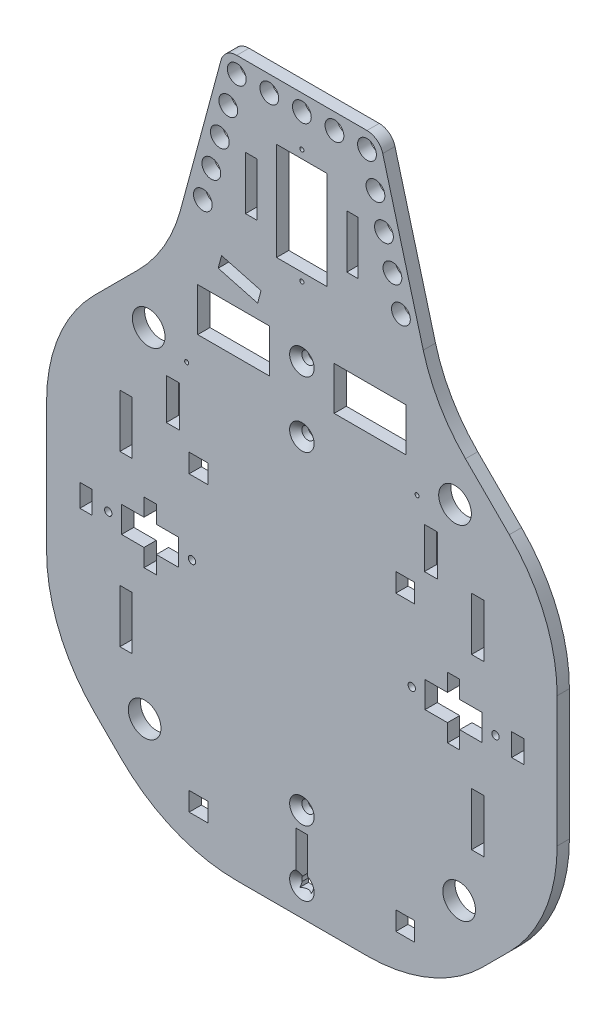
SolidWorks part; units mm, degrees
other "Popis1"
sketch "Skica4" plane through (-62.5, 107.5, 3) normal (-0.0791, 0.0312, 0.9964) x (0.9969, 0.0058, 0.079)
sketch "Skica5" plane through (-62.5, 107.5, 3) normal (-0.0791, 0.0312, 0.9964) x (0.9969, 0.0058, 0.079)
sketch "Skica6" plane through (-62.5, 112.5, 3) normal (-0.0791, 0.0312, 0.9964) x (0.9969, 0.0058, 0.079)
ref_plane "Přední rovina" through (0, 0, 0) normal (0, 0, 1) x (1, 0, 0)
ref_plane "Horní rovina" through (0, 0, 0) normal (0, 1, 0) x (1, 0, 0)
ref_plane "Pravá rovina" through (0, 0, 0) normal (1, 0, 0) x (0, 0, -1)
sketch "Skica1" plane through (0, 0, 0) normal (0, 0, 1) x (1, 0, 0)
  line L0 (-334.3708, 0) -> (16384.1714, 0) construction
  line L1 (0, -334.3708) -> (0, 16384.1714) construction
  line L2 (-44.3956, 7.5) -> (-44.3956, -7.5) construction
  line L3 (-62.5, -62.5) -> (62.5, -62.5) construction
  line L4 (-62.5, -62.5) -> (-62.5, 62.5) construction
  line L5 (-62.5, 62.5) -> (62.5, 62.5) construction
  line L6 (62.5, -62.5) -> (62.5, 62.5) construction
  line L7 (-62.5, -62.5) -> (62.5, 62.5) construction
  line L8 (-62.5, 62.5) -> (62.5, -62.5) construction
  line L9 (-44.3956, 7.5) -> (-61.3, 7.5) construction
  line L10 (-41.5478, 0) -> (-41.5478, 14.2) construction
  line L11 (-44.1478, 3.2) -> (-38.6478, 3.2)
  line L13 (-44.5478, 27.2) -> (-41.5478, 27.2)
  line L14 (-44.5478, 27.2) -> (-44.5478, 14.2)
  line L15 (-44.5478, 14.2) -> (-41.5478, 14.2)
  line L16 (-41.5478, 27.2) -> (-41.5478, 14.2)
  line L20 (-54.3478, 2.75) -> (-51.3478, 2.75)
  line L21 (-54.3478, 2.75) -> (-54.3478, -2.75)
  line L22 (-54.3478, -2.75) -> (-51.3478, -2.75)
  line L23 (-51.3478, 2.75) -> (-51.3478, -2.75)
  line L24 (-54.3478, 2.75) -> (-51.3478, -2.75) construction
  line L25 (-54.3478, -2.75) -> (-51.3478, 2.75) construction
  line L26 (-44.1478, 3.2) -> (-30.1478, 3.2) construction
  line L27 (-44.1478, 3.2) -> (-44.1478, -3.2)
  line L28 (-44.1478, -3.2) -> (-30.1478, -3.2) construction
  line L29 (-30.1478, 3.2) -> (-30.1478, -3.2)
  line L30 (-44.1478, 3.2) -> (-30.1478, -3.2) construction
  line L31 (-44.1478, -3.2) -> (-30.1478, 3.2) construction
  line L32 (-38.6478, -7.5) -> (-35.6478, -7.5)
  line L33 (-38.6478, -7.5) -> (-38.6478, 7.5) construction
  line L34 (-38.6478, 7.5) -> (-35.6478, 7.5)
  line L35 (-35.6478, -7.5) -> (-35.6478, 7.5) construction
  line L36 (-38.6478, -7.5) -> (-35.6478, 7.5) construction
  line L37 (-38.6478, 7.5) -> (-35.6478, -7.5) construction
  line L38 (-38.6478, 3.2) -> (-38.6478, 7.5)
  line L39 (-35.6478, 7.5) -> (-35.6478, 3.2)
  line L40 (-35.6478, 3.2) -> (-30.1478, 3.2)
  line L41 (-30.1478, -3.2) -> (-35.6478, -3.2)
  line L42 (-35.6478, -3.2) -> (-35.6478, -7.5)
  line L43 (-38.6478, -7.5) -> (-38.6478, -3.2)
  line L44 (-38.6478, -3.2) -> (-44.1478, -3.2)
  line L45 (-41.5478, -27.2) -> (-41.5478, -14.2)
  line L46 (-44.5478, -27.2) -> (-41.5478, -27.2)
  line L47 (-44.5478, -27.2) -> (-44.5478, -14.2)
  line L48 (-44.5478, -14.2) -> (-41.5478, -14.2)
  line L49 (-62.5, -32.5) -> (-62.5, 32.5)
  line L50 (-62.5, 32.5) -> (-32.5, 62.5)
  line L51 (-62.5, -32.5) -> (-32.5, -62.5)
  line L52 (-32.5, -62.5) -> (32.5, -62.5)
  line L54 (38.6478, -7.5) -> (35.6478, -7.5)
  line L55 (38.6478, -7.5) -> (38.6478, -3.2)
  line L56 (35.6478, -3.2) -> (35.6478, -7.5)
  line L57 (30.1478, -3.2) -> (35.6478, -3.2)
  line L58 (38.6478, -3.2) -> (44.1478, -3.2)
  line L59 (30.1478, 3.2) -> (30.1478, -3.2)
  line L60 (35.6478, 3.2) -> (30.1478, 3.2)
  line L61 (38.6478, 7.5) -> (35.6478, 7.5)
  line L62 (35.6478, 7.5) -> (35.6478, 3.2)
  line L63 (38.6478, 3.2) -> (38.6478, 7.5)
  line L64 (44.1478, 3.2) -> (44.1478, -3.2)
  line L65 (44.1478, 3.2) -> (38.6478, 3.2)
  line L66 (51.3478, 2.75) -> (51.3478, -2.75)
  line L67 (54.3478, -2.75) -> (51.3478, -2.75)
  line L68 (54.3478, 2.75) -> (54.3478, -2.75)
  line L69 (54.3478, 2.75) -> (51.3478, 2.75)
  line L70 (41.5478, 27.2) -> (41.5478, 14.2)
  line L71 (44.5478, 14.2) -> (41.5478, 14.2)
  line L72 (44.5478, 27.2) -> (44.5478, 14.2)
  line L73 (44.5478, 27.2) -> (41.5478, 27.2)
  line L74 (44.5478, -14.2) -> (41.5478, -14.2)
  line L75 (44.5478, -27.2) -> (44.5478, -14.2)
  line L76 (44.5478, -27.2) -> (41.5478, -27.2)
  line L77 (41.5478, -27.2) -> (41.5478, -14.2)
  line L78 (62.5, -32.5) -> (32.5, -62.5)
  line L79 (62.5, -32.5) -> (62.5, 32.5)
  line L80 (62.5, 32.5) -> (32.5, 62.5)
  line L81 (25.5, 59.1) -> (25.5, 48.5)
  line L86 (-8.8, 34.1) -> (8.8, 23.5) construction
  line L87 (-8.8, 23.5) -> (8.8, 34.1) construction
  line L88 (-25.5, 59.1) -> (-7.9, 59.1)
  line L89 (-25.5, 59.1) -> (-25.5, 48.5)
  line L90 (-25.5, 48.5) -> (-7.9, 48.5)
  line L91 (-7.9, 59.1) -> (-7.9, 48.5)
  line L92 (7.9, 59.1) -> (7.9, 48.5)
  line L93 (25.5, 48.5) -> (7.9, 48.5)
  line L94 (25.5, 59.1) -> (7.9, 59.1)
  line L95 (-6.2, 74.5) -> (-6.2, 98.5)
  line L96 (-6.2, 98.5) -> (6.2, 98.5)
  line L97 (6.2, 98.5) -> (6.2, 74.5)
  line L98 (6.2, 74.5) -> (-6.2, 74.5)
  line L99 (-11, 93) -> (-11, 80)
  line L100 (-11, 80) -> (-13.8, 80)
  line L101 (-13.8, 80) -> (-13.8, 93)
  line L102 (-13.8, 93) -> (-11, 93)
  line L107 (-20.4875, 65.0882) -> (-10.8282, 62.5)
  line L108 (-10.8282, 62.5) -> (-10, 65.591)
  line L109 (-10, 65.591) -> (-19.6593, 68.1792)
  line L110 (-19.6593, 68.1792) -> (-20.4875, 65.0882)
  line L111 (-6.2, 86.5) -> (6.2, 86.5) construction
  line L112 (-6.2, 86.5) -> (-11, 86.5) construction
  line L113 (11, 80) -> (13.8, 80)
  line L114 (11, 93) -> (11, 80)
  line L115 (13.8, 93) -> (11, 93)
  line L116 (13.8, 80) -> (13.8, 93)
  line L117 (30, 26) -> (33.2, 26)
  line L118 (-30, 36) -> (-33.2, 36)
  line L119 (-30, 36) -> (-30, 26)
  line L120 (-30, 26) -> (-33.2, 26)
  line L121 (-33.2, 36) -> (-33.2, 26)
  line L122 (33.2, 36) -> (33.2, 26)
  line L123 (30, 36) -> (33.2, 36)
  line L124 (30, 36) -> (30, 26)
  line L125 (-32.5, 62.5) -> (-19.0034, 112.5)
  line L126 (-19.0034, 112.5) -> (19.0034, 112.5)
  line L129 (0, 108.5) -> (7.97, 108.5) construction
  line L137 (32.5, 62.5) -> (19.0034, 112.5)
  line L138 (-15.94, 108.5) -> (-28.3568, 62.5) construction
  line L140 (-25.3, -51.5) -> (25.3, -51.5) construction
  line L141 (-25.3, -51.5) -> (-25.3, 20.23) construction
  line L142 (-25.3, 20.23) -> (25.3, 20.23) construction
  line L143 (25.3, -51.5) -> (25.3, 20.23) construction
  line L144 (-25.3, -51.5) -> (25.3, 20.23) construction
  line L145 (-25.3, 20.23) -> (25.3, -51.5) construction
  line L146 (-25.3, -15.635) -> (25.3, -15.635) construction
  line L147 (23, 22.53) -> (27.6, 22.53)
  line L148 (23, 22.53) -> (23, 17.93)
  line L149 (23, 17.93) -> (27.6, 17.93)
  line L150 (27.6, 22.53) -> (27.6, 17.93)
  line L151 (23, 22.53) -> (27.6, 17.93) construction
  line L152 (23, 17.93) -> (27.6, 22.53) construction
  line L153 (23, -49.2) -> (27.6, -49.2)
  line L154 (27.6, -53.8) -> (27.6, -49.2)
  line L155 (23, -53.8) -> (27.6, -53.8)
  line L156 (23, -53.8) -> (23, -49.2)
  line L157 (-23, -53.8) -> (-27.6, -53.8)
  line L158 (-23, -53.8) -> (-23, -49.2)
  line L159 (-27.6, -53.8) -> (-27.6, -49.2)
  line L160 (-23, -49.2) -> (-27.6, -49.2)
  line L161 (-23, 22.53) -> (-23, 17.93)
  line L162 (-23, 22.53) -> (-27.6, 22.53)
  line L163 (-27.6, 22.53) -> (-27.6, 17.93)
  line L164 (-23, 17.93) -> (-27.6, 17.93)
  line L165 (37.1478, 7.5) -> (37.1478, -7.5) construction
  circle A0 centre (-52.8478, 0) radius 11.3 construction
  circle A1 centre (0, 100.5) radius 0.5
  circle A3 centre (0, 72.5) radius 0.5
  circle A4 centre (0, 108.5) radius 2.3
  circle A5 centre (7.97, 108.5) radius 2.3
  circle A6 centre (15.94, 108.5) radius 2.3
  circle A7 centre (-15.94, 108.5) radius 2.3
  circle A8 centre (-7.97, 108.5) radius 2.3
  circle A9 centre (-15.94, 108.5) radius 2.3 construction
  circle A10 centre (-18.017, 100.8054) radius 2.3
  circle A11 centre (-20.094, 93.1108) radius 2.3
  circle A12 centre (-22.171, 85.4162) radius 2.3
  circle A13 centre (-24.2481, 77.7216) radius 2.3
  circle A14 centre (24.2481, 77.7216) radius 2.3
  circle A15 centre (22.171, 85.4162) radius 2.3
  circle A16 centre (20.094, 93.1108) radius 2.3
  circle A17 centre (18.017, 100.8054) radius 2.3
  circle A18 centre (47.3978, 0) radius 0.9
  circle A19 centre (26.8978, 0) radius 0.9
  circle A20 centre (-47.3978, 0) radius 0.9
  circle A21 centre (-26.8978, 0) radius 0.9
  point P4 (0, 0)
  point P15 (-52.8478, 0)
  point P17 (-37.1478, 0)
  point P27 (-37.1478, 0)
  point P46 (52.8478, 0)
  point P48 (0, 28.8)
  point P49 (0, -62.5)
  point P78 (0, 62.5)
  point P138 (0, 112.5)
  point P149 (-15.94, 108.5)
  point P156 (0, -15.635)
  dimension "D3" = 13
  dimension "D6" = 22.6
  dimension "D30" = 1
  dimension "D40" = 4.6
  dimension "D44" = 4
  dimension "D53" = 1.8
  dimension "D1" = 125
  dimension "D2" = 125
  dimension "D4" = 3
  dimension "D5" = 14.2
  dimension "D7" = 15
  dimension "D8" = 1.2
  dimension "D9" = 3
  dimension "D10" = 5.5
  dimension "D11" = 6.8
  dimension "D12" = 14
  dimension "D13" = 6.4
  dimension "D14" = 3
  dimension "D15" = 15
  dimension "D17" = 65
  dimension "D18" = 45
  dimension "D20" = 17.6
  dimension "D21" = 10.6
  dimension "D22" = 7.9
  dimension "D24" = 12.4
  dimension "D25" = 24
  dimension "D26" = 13
  dimension "D27" = 2.8
  dimension "D28" = 11
  dimension "D29" = 12
  dimension "D31" = 2
  dimension "D32" = 10
  dimension "D33" = 3.2
  dimension "D34" = 10
  dimension "D35" = 15
  dimension "D36" = 3.2
  dimension "D37" = 10
  dimension "D38" = 30
  dimension "D39" = 26
  dimension "D42" = 7.97
  dimension "D43" = 4
  dimension "D45" = 8
  dimension "D46" = 74.894
  dimension "D47" = 2
  dimension "D48" = 71.73
  dimension "D49" = 50.6
  dimension "D50" = 11
  dimension "D51" = 4.6
  dimension "D52" = 10.25
  dimension "D54" = 14.2
  dimension "D41" = 3
extrude "Přidat vysunutím1" add sketch "Skica1" along normal blind 3
sketch "Skica2" plane through (0, 0, 0) normal (0, 0, 1) x (1, 0, 0)
  line L0 (0, -1000) -> (0, 49000) construction
  line L1 (-1000, 0) -> (49000, 0) construction
  line L2 (8.8, 34.1) -> (-8.8, 34.1) construction
  circle A0 centre (0, 39.6) radius 1.5
  circle A1 centre (0, 55.6) radius 1.5
  circle A2 centre (0, -55.6) radius 1.5
  circle A3 centre (0, -39.6) radius 1.5
  dimension "D3" = 3
  dimension "D1" = 5.5
  dimension "D2" = 16
extrude "Odebrat vysunutím1" cut sketch "Skica2" along normal up to surface (3 mm away) up to face at (-25.3, -51.5, 3)
chamfer "Zkosení1" distance 1.5 angle 45 4 edges at (-1.5, -55.6, 3) (-1.5, -39.6, 3) (-1.5, 39.6, 3) (-1.5, 55.6, 3)
fillet "Zaoblit1" radius 40 8 edges at (-62.5, -32.5, 1.5) (-32.5, -62.5, 1.5) (32.5, -62.5, 1.5) (62.5, -32.5, 1.5) (62.5, 32.5, 1.5) (-62.5, 32.5, 1.5) (32.5, 62.5, 1.5) (-32.5, 62.5, 1.5)
fillet "Zaoblit2" radius 4 2 edges at (19.0034, 112.5, 1.5) (-19.0034, 112.5, 1.5)
sketch "Skica3" plane through (0, 0, 3) normal (0, 0, 1) x (1, 0, 0)
  line L0 (0, -965.9) -> (0, 49034.1) construction
  line L1 (8.8, 34.1) -> (-8.8, 34.1) construction
  line L2 (-11, 93) -> (-13.8, 93) construction
  line L3 (-1.4, -44.1) -> (1.4, -44.1)
  line L4 (-1.4, -44.1) -> (-1.4, -57.1)
  line L5 (-1.4, -57.1) -> (1.4, -57.1)
  line L6 (1.4, -44.1) -> (1.4, -57.1)
  line L7 (-13.8, 93) -> (-13.8, 80) construction
  circle A0 centre (-28.2, 41.3) radius 0.5
  circle A1 centre (28.2, 41.3) radius 0.5
  circle A2 centre (0, -55.6) radius 1.5 construction
  point P5 (0, 34.1)
  dimension "D1" = 1
  dimension "D2" = 28.2
  dimension "D3" = 7.2
extrude "Odebrat vysunutím2" cut sketch "Skica3" against normal through all
sketch "Skica7" plane through (0, 0, 3) normal (0, 0, 1) x (1, 0, 0)
  line L0 (-62.5, 15.9315) -> (-62.5, -15.9315) construction
  line L1 (-15.9315, -62.5) -> (15.9315, -62.5) construction
  line L2 (62.5, -15.9315) -> (62.5, 15.9315) construction
  line L3 (-30, 36) -> (-33.2, 36) construction
  line L4 (-25.5, 59.1) -> (-25.5, 48.5) construction
  line L5 (33.2, 36) -> (30, 36) construction
  line L6 (25.5, 48.5) -> (25.5, 59.1) construction
  circle A0 centre (-38.5, -39.5) radius 4
  circle A1 centre (38.5, -39.5) radius 4
  circle A2 centre (-37.5, 44) radius 4
  circle A3 centre (37.5, 44) radius 4
  dimension "D1" = 24
  dimension "D3" = 24
  dimension "D4" = 8
  dimension "D6" = 8
  dimension "D2" = 23
  dimension "D5" = 12
  dimension "D7" = 12
extrude "Odebrat vysunutím3" cut sketch "Skica7" against normal through all
